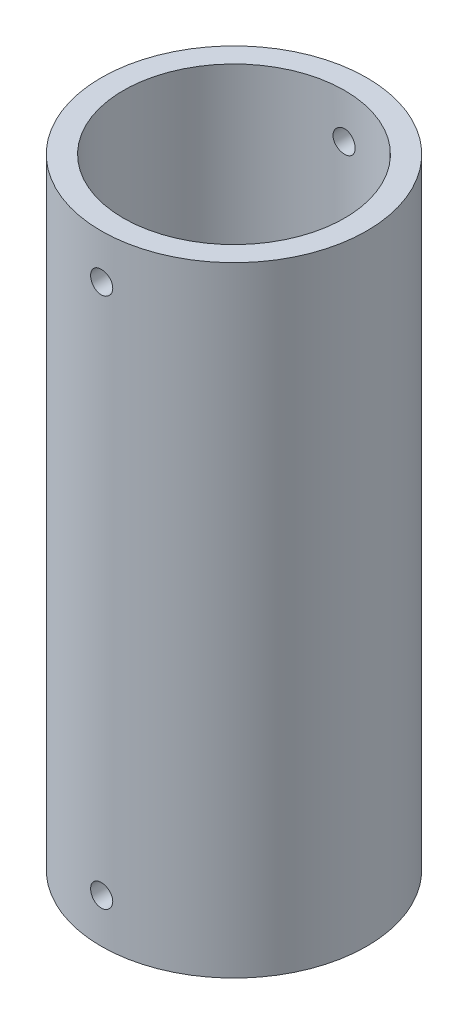
SolidWorks part; units mm, degrees
ref_plane "Front Plane" through (0, 0, 0) normal (0, 0, 1) x (1, 0, 0)
ref_plane "Top Plane" through (0, 0, 0) normal (0, 1, 0) x (1, 0, 0)
ref_plane "Right Plane" through (0, 0, 0) normal (1, 0, 0) x (0, 0, -1)
sketch "Sketch1" plane through (0, 0, 0) normal (0, 1, 0) x (1, 0, 0)
  circle A0 centre (0, 0) radius 31.75
  circle A1 centre (0, 0) radius 38.1
  dimension "D1" = 76.2
  dimension "D2" = 6.35
extrude "Boss-Extrude1" add sketch "Sketch1" along normal blind 177.8
sketch "Sketch2" plane through (0, 0, 0) normal (0, 0, 1) x (1, 0, 0)
  line L0 (-38.1, 0) -> (38.1, 0) construction
  line L1 (38.1, 177.8) -> (-38.1, 177.8) construction
  circle A0 centre (0, 165.1) radius 3.175
  circle A1 centre (0, 12.7) radius 3.175
  dimension "D3" = 6.35
  dimension "D4" = 6.35
  dimension "D1" = 12.7
  dimension "D2" = 12.7
extrude "Cut-Extrude1" cut sketch "Sketch2" against normal through all both and the other way through all
